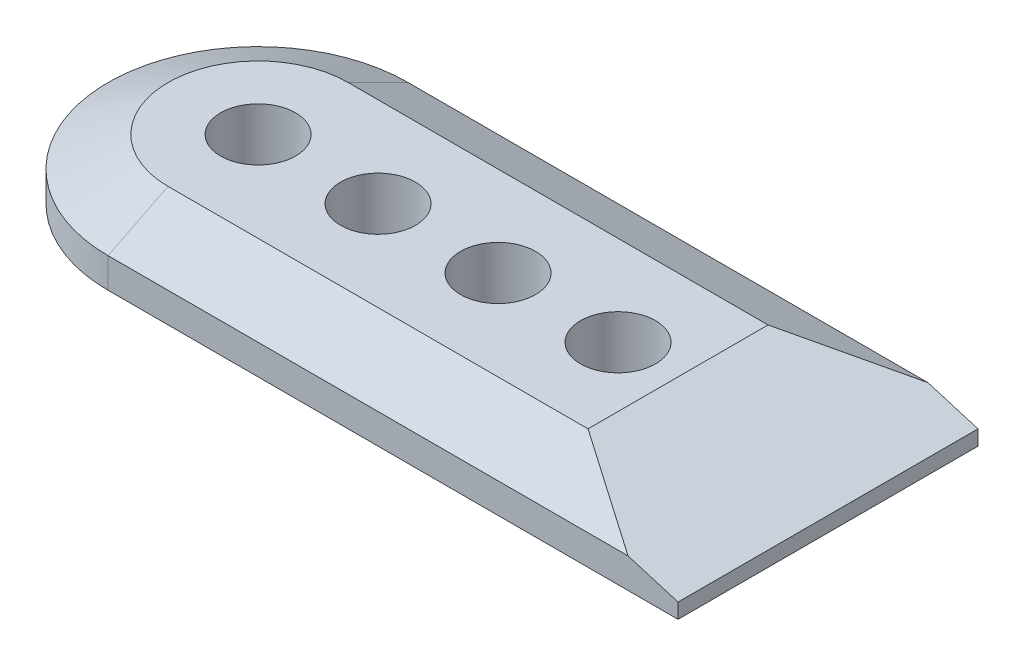
SolidWorks part; units mm, degrees
ref_plane "Front Plane" through (0, 0, 0) normal (0, 0, 1) x (1, 0, 0)
ref_plane "Top Plane" through (0, 0, 0) normal (0, 1, 0) x (1, 0, 0)
ref_plane "Right Plane" through (0, 0, 0) normal (1, 0, 0) x (0, 0, -1)
sketch "Sketch3" plane through (0, 0, 0) normal (0, 1, 0) x (1, 0, 0)
  line L0 (0, 31.75) -> (120.65, 31.75)
  line L1 (120.65, 31.75) -> (120.65, -31.75)
  line L2 (120.65, -31.75) -> (0, -31.75)
  arc A0 (0, 31.75) -> (0, -31.75) centre (0, 0) ccw
  point P6 (0, 0)
  point P7 (0, 0)
  dimension "D1" = 31.75
  dimension "D2" = 120.65
  dimension "D3" = 63.5
extrude "Boss-Extrude2" add sketch "Sketch3" along normal blind 12.7
chamfer "Chamfer3" distance 6.35 distance2 12.7 3 edges at (60.325, 12.7, -31.75) (-31.75, 12.7, 0) (60.325, 12.7, 31.75)
chamfer "Chamfer4" distance 9.525 distance2 31.75 1 edges at (120.65, 12.7, 0)
sketch "Sketch6" plane through (0, 12.7, 0) normal (0, 1, 0) x (1, 0, 0)
  circle A0 centre (0, 0) radius 7.9375
  circle A1 centre (25.4, 0) radius 7.9375
  arc A2 (0, 31.75) -> (0, -31.75) centre (0, 0) ccw construction
  circle A3 centre (50.8, 0) radius 7.9375
  circle A4 centre (76.2, 0) radius 7.9375
  point P2 (0, 0)
  point P7 (-31.75, 0)
  dimension "D2" = 15.875
  dimension "D1" = 31.75
  dimension "D4" = 25.4
  dimension "D3" = 4
extrude "Cut-Extrude1" cut sketch "Sketch6" against normal through all
